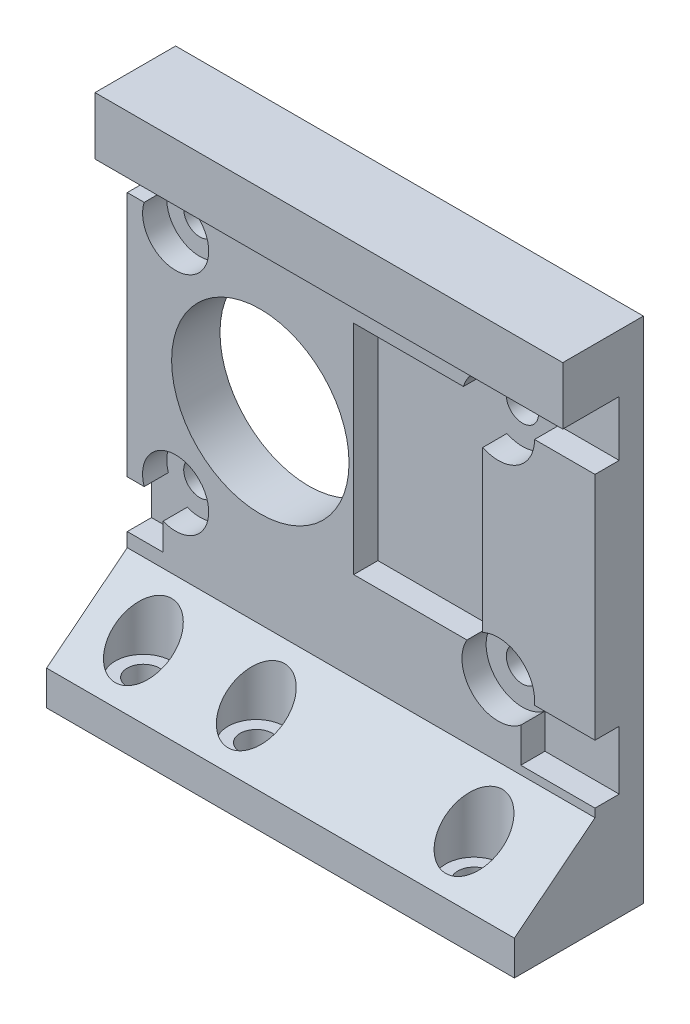
SolidWorks part; units mm, degrees
material "ABS"
ref_plane "Front Plane" through (0, 0, 0) normal (0, 0, 1) x (1, 0, 0)
ref_plane "Top Plane" through (0, 0, 0) normal (0, 1, 0) x (1, 0, 0)
ref_plane "Right Plane" through (0, 0, 0) normal (1, 0, 0) x (0, 0, -1)
sketch "Sketch1" plane through (0, 0, 0) normal (0, 0, 1) x (1, 0, 0)
  line L1 (-76.1871, 64.9281) -> (16.8129, 64.9281)
  line L2 (-76.1871, 64.9281) -> (-76.1871, -35.0719)
  line L3 (-76.1871, -35.0719) -> (16.8129, -35.0719)
  line L4 (16.8129, 64.9281) -> (16.8129, -35.0719)
  dimension "D1" = 93
  dimension "D2" = 100
extrude "Boss-Extrude2" add sketch "Sketch1" along normal blind 10 contours L1 L4 L3 L2
sketch "Sketch3" plane through (0, 0, 0) normal (0, 0, -1) x (-1, 0, 0)
  line L0 (76.1871, -35.0719) -> (-16.8129, -35.0719) construction
  line L1 (-16.8129, 64.9281) -> (-6.8129, 64.9281)
  line L2 (-16.8129, 64.9281) -> (-16.8129, -35.0719)
  line L3 (-16.8129, -35.0719) -> (-6.8129, -35.0719)
  line L4 (-6.8129, 64.9281) -> (-6.8129, -35.0719)
  line L5 (-16.8129, 64.9281) -> (-16.8129, -35.0719) construction
  dimension "D1" = 0
  dimension "D2" = 0
  dimension "D3" = 10
  dimension "D4" = 100
sketch "Sketch4" plane through (16.8129, 0, 0) normal (1, 0, 0) x (0, 0, -1)
  line L0 (-10, 64.9281) -> (-10, -35.0719) construction
  line L1 (-10, -5.0719) -> (0.01, -5.0719)
  line L2 (-10, -5.0719) -> (-10, -20.0719)
  line L3 (-10, -20.0719) -> (0.01, -20.0719)
  line L4 (0.01, -5.0719) -> (0.01, -20.0719)
  line L6 (-10, -35.0719) -> (0, -35.0719) construction
  dimension "D1" = 15
  dimension "D2" = 15
extrude "Boss-Extrude4" add sketch "Sketch4" along normal blind 24
sketch "Sketch5" plane through (0, -5.0719, 0) normal (0, 1, 0) x (1, 0, 0)
  line L0 (40.8129, -10) -> (16.8129, -10) construction
  line L2 (16.8129, 0) -> (16.8129, -10) construction
  circle A0 centre (26.8129, -5) radius 2
  dimension "D2" = 4
  dimension "D3" = 10
  dimension "D1" = 5
extrude "Cut-Extrude1" cut sketch "Sketch5" against normal blind 50
sketch "Sketch6" plane through (0, 0, 10) normal (0, 0, -1) x (-1, 0, 0)
  line L2 (76.1871, -35.0719) -> (-16.8129, -35.0719) construction
  line L3 (-16.8129, 64.9281) -> (-16.8129, -35.0719) construction
  circle A0 centre (-1.8129, -24.5719) radius 7.5
  dimension "D1" = 15
  dimension "D2" = 10.5
  dimension "D3" = 15
sketch "Sketch7" plane through (0, 0, 0) normal (0, 0, -1) x (-1, 0, 0)
  circle A0 centre (24.1871, 36.9281) radius 11
  circle A1 centre (24.1871, 36.9281) radius 9.3 construction
  dimension "D1" = 22
extrude "Cut-Extrude3" cut sketch "Sketch7" against normal blind 50
sketch "Sketch14" plane through (0, 0, 10) normal (0, 0, 1) x (1, 0, 0)
  line L0 (16.8129, 64.9281) -> (16.8129, -5.0719) construction
  line L1 (-44.6871, 15.7891) -> (16.8129, 15.7891)
  line L2 (-44.6871, 15.7891) -> (-44.6871, 57.7891)
  line L3 (-44.6871, 57.7891) -> (16.8129, 57.7891)
  line L4 (16.8129, 15.7891) -> (16.8129, 57.7891)
  dimension "D1" = 42
  dimension "D3" = 61.5
extrude "Cut-Extrude8" cut sketch "Sketch14" against normal blind 4
sketch "Sketch15" plane through (0, 0, 0) normal (0, 0, -1) x (-1, 0, 0)
  circle A0 centre (24.1871, 36.9281) radius 10
  circle A1 centre (24.1871, 36.9281) radius 11 construction
  dimension "D1" = 20
  dimension "D2" = 0
sketch "Sketch16" plane through (0, 0, 10) normal (0, 0, 1) x (1, 0, 0)
  line L0 (-43.6871, 56.9281) -> (14.3129, 56.9281) construction
  line L1 (-44.1871, 57.3281) -> (16.8129, 57.3281)
  line L2 (-44.1871, 57.3281) -> (-44.1871, 64.9281)
  line L3 (-44.1871, 64.9281) -> (16.8129, 64.9281)
  line L4 (16.8129, 57.3281) -> (16.8129, 64.9281)
  dimension "D1" = 0.4
sketch "Sketch17" plane through (0, 0, 10) normal (0, 0, 1) x (1, 0, 0)
  line L0 (16.8129, 15.7891) -> (16.8129, -5.0719) construction
  line L1 (-44.1871, 16.7281) -> (16.8129, 16.7281)
  line L2 (-44.1871, 16.7281) -> (-44.1871, -20.0719)
  line L3 (-44.1871, -20.0719) -> (16.8129, -20.0719)
  line L4 (16.8129, 16.7281) -> (16.8129, -20.0719)
  line L5 (-43.6871, 16.9281) -> (14.3129, 16.9281) construction
  line L6 (40.8129, -20.0719) -> (16.8129, -20.0719) construction
  line L9 (16.8129, -20.0719) -> (40.8129, -20.0719)
  line L10 (16.8129, -20.0719) -> (16.8129, -5.0719)
  line L11 (16.8129, -5.0719) -> (40.8129, -5.0719)
  line L12 (40.8129, -20.0719) -> (40.8129, -5.0719)
  line L13 (16.8129, -20.0719) -> (40.8129, -5.0719) construction
  line L14 (16.8129, -5.0719) -> (40.8129, -20.0719) construction
  point P16 (28.8129, -12.5719)
  dimension "D1" = 0.2
  dimension "D2" = 0
sketch "Sketch19" plane through (0, 0, 0) normal (0, 0, -1) x (-1, 0, 0)
  line L1 (-16.8129, 64.9281) -> (-16.8129, -35.0719) construction
  circle A0 centre (53.1871, 36.9281) radius 11
  circle A1 centre (24.1871, 36.9281) radius 10 construction
  dimension "D1" = 22
  dimension "D3" = 0
  dimension "D2" = 70
extrude "Cut-Extrude11" cut sketch "Sketch19" against normal blind 15
sketch "Sketch20" plane through (0, 0, 6) normal (0, 0, 1) x (1, 0, 0)
  circle A0 centre (-34.6871, 50.9281) radius 2
  circle A1 centre (5.3129, 50.9281) radius 2
  circle A2 centre (-34.6871, 22.9281) radius 2
  circle A3 centre (5.3129, 22.9281) radius 2
  arc A5 (-27.0471, 34.1316) -> (-27.0471, 39.7246) centre (-24.1871, 36.9281) ccw construction
  circle A6 centre (-24.1871, 36.9281) radius 11 construction
  dimension "D1" = 4
  dimension "D2" = 4
  dimension "D3" = 4
  dimension "D4" = 4
  dimension "D5" = 0
  dimension "D6" = 28
  dimension "D7" = 0
  dimension "D8" = 40
  dimension "D9" = 14
  dimension "D10" = 10.5
  dimension "D11" = 28
  dimension "D12" = 40
extrude "Cut-Extrude12" cut sketch "Sketch20" against normal blind 10
sketch "Sketch8" plane through (0, 64.9281, 0) normal (0, 1, 0) x (1, 0, 0)
  line L0 (-76.1871, -10) -> (16.8129, -10) construction
  line L5 (16.8129, 0) -> (12.3014, -10) construction
  line L6 (16.8129, -10) -> (7.8859, 0) construction
  line L8 (16.8129, -10) -> (16.8129, 0) construction
  line L9 (-76.1871, 0) -> (16.8129, 0) construction
  circle A0 centre (11.8129, -7) radius 1.4
  circle A1 centre (-13.1871, -7) radius 1.4
  point P4 (13.816, -6.6429)
  dimension "D1" = 25
  dimension "D2" = 5
  dimension "D3" = 2.8
  dimension "D4" = 7
  dimension "D5" = 7
sketch "Sketch21" plane through (0, 0, 0) normal (0, 0, -1) x (-1, 0, 0)
  line L1 (76.1871, 64.9281) -> (36.1871, 64.9281)
  line L2 (76.1871, 64.9281) -> (76.1871, 58.9281)
  line L3 (76.1871, 58.9281) -> (36.1871, 58.9281)
  line L4 (36.1871, 64.9281) -> (36.1871, 58.9281)
  dimension "D1" = 6
  dimension "D2" = 40
extrude "Boss-Extrude5" add sketch "Sketch21" along normal blind 27
sketch "Sketch22" plane through (0, 58.9281, 0) normal (0, -1, 0) x (1, 0, 0)
  line L0 (-76.1871, -27) -> (-76.1871, 0) construction
  line L1 (-36.1871, -27) -> (-76.1871, -27)
  line L2 (-36.1871, -27) -> (-36.1871, -20.7)
  line L3 (-36.1871, -20.7) -> (-76.1871, -20.7)
  line L4 (-76.1871, -27) -> (-76.1871, -20.7)
  dimension "D1" = 6.3
extrude "Boss-Extrude7" add sketch "Sketch22" along normal blind 40
sketch "Sketch23" plane through (0, 0, 10) normal (0, 0, 1) x (1, 0, 0)
  circle A0 centre (-53.1871, 36.9281) radius 8
  arc A1 (-44.6871, 43.9102) -> (-44.6871, 29.9459) centre (-53.1871, 36.9281) ccw construction
  dimension "D1" = 16
  dimension "D2" = 0
extrude "Cut-Extrude13" cut sketch "Sketch23" against normal blind 40
sketch "Sketch24" plane through (0, 0, 10) normal (0, 0, 1) x (1, 0, 0)
  line L1 (-76.1871, -35.0719) -> (42.0908, -35.0719)
  line L2 (-76.1871, -35.0719) -> (-76.1871, 6.7281)
  line L3 (-76.1871, 6.7281) -> (42.0908, 6.7281)
  line L4 (42.0908, -35.0719) -> (42.0908, 6.7281)
  dimension "D1" = 41.8
extrude "Cut-Extrude14" cut sketch "Sketch24" against normal blind 40
sketch "Sketch25" plane through (0, 0, 10) normal (0, 0, 1) x (1, 0, 0)
  line L5 (-44.6871, 29.9459) -> (-44.6871, 15.7891) construction
  line L6 (-76.1871, 6.7281) -> (-44.6871, 6.7281)
  line L7 (-76.1871, 6.7281) -> (-76.1871, 29.9281)
  line L8 (-76.1871, 29.9281) -> (-44.6871, 29.9281)
  line L9 (-44.6871, 6.7281) -> (-44.6871, 29.9281)
  arc A2 (-44.6871, 43.9102) -> (-44.6871, 29.9459) centre (-53.1871, 36.9281) ccw construction
  dimension "D1" = 7
extrude "Cut-Extrude15" cut sketch "Sketch25" against normal blind 20
sketch "Sketch26" plane through (0, 0, 6) normal (0, 0, 1) x (1, 0, 0)
  line L1 (-44.6871, 15.7891) -> (-36.2375, 15.7891)
  line L2 (-44.6871, 15.7891) -> (-44.6871, 21.6647)
  line L3 (-44.6871, 21.6647) -> (-36.2375, 21.6647)
  line L4 (-36.2375, 15.7891) -> (-36.2375, 21.6647)
  line L5 (-44.6871, 57.7891) -> (-36.2375, 57.7891)
  line L6 (-44.6871, 57.7891) -> (-44.6871, 52.1914)
  line L7 (-44.6871, 52.1914) -> (-36.2375, 52.1914)
  line L8 (-36.2375, 57.7891) -> (-36.2375, 52.1914)
  line L9 (6.8634, 52.1914) -> (14.3021, 52.1914)
  line L10 (6.8634, 52.1914) -> (6.8634, 57.7891)
  line L11 (6.8634, 57.7891) -> (14.3021, 57.7891)
  line L12 (14.3021, 52.1914) -> (14.3021, 57.7891)
  line L13 (6.8634, 20.9281) -> (14.3021, 20.9281)
  line L14 (6.8634, 20.9281) -> (6.8634, 15.7891)
  line L15 (6.8634, 15.7891) -> (14.3021, 15.7891)
  line L16 (14.3021, 20.9281) -> (14.3021, 15.7891)
  circle A0 centre (-34.6871, 22.9281) radius 2 construction
  circle A1 centre (-34.6871, 50.9281) radius 2 construction
  circle A2 centre (5.3129, 50.9281) radius 2 construction
  circle A3 centre (5.3129, 22.9281) radius 4
  circle A4 centre (5.3129, 50.9281) radius 4
  circle A5 centre (-34.6871, 50.9281) radius 4
  circle A6 centre (-34.6871, 22.9281) radius 4
  circle A7 centre (5.3129, 50.9281) radius 4
  circle A8 centre (5.3129, 22.9281) radius 4
  circle A9 centre (-34.6871, 50.9281) radius 4
  circle A10 centre (-34.6871, 22.9281) radius 4
  line M5 (-44.6871, 57.7891) -> (-44.6871, 43.9102)
  line M8 (-44.6871, 29.9281) -> (-44.6871, 15.7891)
  line M9 (-44.6871, 15.7891) -> (16.8129, 15.7891)
  line M11 (16.8129, 57.7891) -> (-44.6871, 57.7891)
  dimension "D1" = 8
  dimension "D2" = 8
  dimension "D3" = 8
  dimension "D4" = 8
extrude "Cut-Extrude18" cut sketch "Sketch26" against normal blind 3 contours A4 L9 L12 L10 M11 | A3 L14 L16 L13 M9 | A5 L8 L7 M11 M5 | A6 L3 L4 M8 M9
sketch "Sketch27" plane through (0, 0, 6) normal (0, 0, 1) x (1, 0, 0)
  circle A0 centre (5.3129, 50.9281) radius 4.1
  circle A1 centre (5.3129, 22.9281) radius 4
  circle A2 centre (-34.6871, 50.9281) radius 4.1
  circle A3 centre (-34.6871, 22.9281) radius 4.1
  dimension "D1" = 8.2
  dimension "D2" = 8.2
  dimension "D3" = 8
  dimension "D4" = 8.2
extrude "Cut-Extrude29" cut sketch "Sketch27" against normal blind 3
sketch "Sketch28" plane through (0, 0, 0) normal (0, 0, -1) x (-1, 0, 0)
  line L5 (-16.8129, 6.7281) -> (44.6871, 6.7281) construction
  line L6 (-16.8129, 64.9281) -> (12.6871, 64.9281)
  line L7 (-16.8129, 64.9281) -> (-16.8129, 6.7281)
  line L8 (-16.8129, 6.7281) -> (12.6871, 6.7281)
  line L9 (12.6871, 64.9281) -> (12.6871, 6.7281)
  circle A1 centre (34.6871, 22.9281) radius 2 construction
  dimension "D1" = 22
extrude "Cut-Extrude30" cut sketch "Sketch28" against normal blind 23
sketch "Sketch29" plane through (0, 15.7891, 0) normal (0, 1, 0) x (1, 0, 0)
  line L1 (-44.6871, -10) -> (-12.6871, -10)
  line L2 (-44.6871, -10) -> (-44.6871, -6)
  line L3 (-44.6871, -6) -> (-12.6871, -6)
  line L4 (-12.6871, -10) -> (-12.6871, -6)
extrude "Cut-Extrude31" cut sketch "Sketch29" against normal blind 23
sketch "Sketch31" plane through (0, 6.7281, 0) normal (0, -1, 0) x (1, 0, 0)
  line L1 (-44.6871, 6) -> (-12.6871, 6)
  line L2 (-44.6871, 6) -> (-44.6871, 0)
  line L3 (-44.6871, 0) -> (-12.6871, 0)
  line L4 (-12.6871, 6) -> (-12.6871, 0)
extrude "Boss-Extrude9" add sketch "Sketch31" along normal blind 6.6
sketch "Sketch32" plane through (0, 0, 6) normal (0, 0, 1) x (1, 0, 0)
  line L0 (-12.6871, 0.1281) -> (-12.6871, 57.7891) construction
  line L1 (-44.6871, 0.1281) -> (-12.6871, 0.1281)
  line L2 (-44.6871, 0.1281) -> (-44.6871, 6.1281)
  line L3 (-44.6871, 6.1281) -> (-12.6871, 6.1281)
  line L4 (-12.6871, 0.1281) -> (-12.6871, 6.1281)
  dimension "D1" = 6
extrude "Boss-Extrude10" add sketch "Sketch32" along normal blind 10
sketch "Sketch33" plane through (0, 6.1281, 0) normal (0, 1, 0) x (1, 0, 0)
  line L0 (-12.6871, -16) -> (-44.6871, -16) construction
  line L1 (-44.6871, -16) -> (-44.6871, -6) construction
  line L2 (-12.6871, -16) -> (-12.6871, -6) construction
  circle A0 centre (-33.6871, -11) radius 2
  circle A1 centre (-19.6871, -11) radius 2
  point P8 (-44.6871, -11)
  dimension "D1" = 4
  dimension "D2" = 4
  dimension "D3" = 0
  dimension "D4" = 5
  dimension "D5" = 11
  dimension "D6" = 7
extrude "Cut-Extrude32" cut sketch "Sketch33" against normal blind 10
sketch "Sketch34" plane through (-12.6871, 0, 0) normal (1, 0, 0) x (0, 0, -1)
  line L0 (-16, 6.1281) -> (-6, 6.1281)
  line L1 (-6, 6.1281) -> (-6, 14.0584)
  line L2 (-6, 6.1281) -> (-6, 57.7891) construction
  line L3 (-6, 14.0584) -> (-16, 6.1281)
extrude "Boss-Extrude11" add sketch "Sketch34" against normal up to vertex
sketch "Sketch35" plane through (0, 6.1281, 0) normal (0, -1, 0) x (1, 0, 0)
  circle A0 centre (-19.6871, 11) radius 3.5
  circle A1 centre (-33.6871, 11) radius 3.5
  dimension "D1" = 7
  dimension "D2" = 7
extrude "Cut-Extrude33" cut sketch "Sketch35" against normal blind 10
sketch "Sketch36" plane through (-36.1871, 0, 0) normal (1, 0, 0) x (0, 0, -1)
  line L1 (0, 64.9281) -> (27, 64.9281)
  line L2 (0, 64.9281) -> (0, 18.9281)
  line L3 (0, 18.9281) -> (27, 18.9281)
  line L4 (27, 64.9281) -> (27, 18.9281)
extrude "Cut-Extrude34" cut sketch "Sketch36" against normal blind 50
sketch "Sketch38" plane through (0, 0, 10) normal (0, 0, 1) x (1, 0, 0)
  line L0 (-76.1871, 64.9281) -> (-12.6871, 64.9281) construction
  line L1 (-76.1871, 29.9281) -> (-44.4371, 29.9281)
  line L2 (-76.1871, 29.9281) -> (-76.1871, 64.9281)
  line L3 (-76.1871, 64.9281) -> (-44.4371, 64.9281)
  line L4 (-44.4371, 29.9281) -> (-44.4371, 64.9281)
extrude "Cut-Extrude35" cut sketch "Sketch38" against normal blind 50
sketch "Sketch40" plane through (0, 0, 16) normal (0, 0, 1) x (1, 0, 0)
  line L1 (-44.6871, 0.1281) -> (-40.6871, 0.1281)
  line L2 (-44.6871, 0.1281) -> (-44.6871, 77.9464)
  line L3 (-44.6871, 77.9464) -> (-40.6871, 77.9464)
  line L4 (-40.6871, 0.1281) -> (-40.6871, 77.9464)
  dimension "D1" = 4
extrude "Cut-Extrude37" cut sketch "Sketch40" against normal blind 110
sketch "Sketch41" plane through (0, 0, 16) normal (0, 0, 1) x (1, 0, 0)
  line L1 (-40.6871, 0.1281) -> (-12.6871, 0.1281)
  line L2 (-40.6871, 0.1281) -> (-40.6871, 1.8481)
  line L3 (-40.6871, 1.8481) -> (-12.6871, 1.8481)
  line L4 (-12.6871, 0.1281) -> (-12.6871, 1.8481)
  dimension "D1" = 1.72
extrude "Cut-Extrude38" cut sketch "Sketch41" against normal blind 50
sketch "Sketch42" plane through (-12.6871, 0, 0) normal (1, 0, 0) x (0, 0, -1)
  line L0 (-10, 64.9281) -> (0, 64.9281)
  line L1 (0, 64.9281) -> (0, 1.8481)
  line L2 (0, 1.8481) -> (-16, 1.8481)
  line L3 (-16, 1.8481) -> (-16, 6.1281)
  line L4 (-16, 6.1281) -> (-6, 14.0584)
  line L5 (-6, 14.0584) -> (-6, 57.7891)
  line L6 (-6, 57.7891) -> (-10, 57.7891)
  line L7 (-10, 57.7891) -> (-10, 64.9281)
extrude "Boss-Extrude12" add sketch "Sketch42" along normal blind 30
sketch "Sketch43" plane through (0, 0, 6) normal (0, 0, 1) x (1, 0, 0)
  circle A0 centre (5.3129, 50.9281) radius 2
  circle A1 centre (5.3129, 22.9281) radius 2
  circle A2 centre (-34.6871, 50.9281) radius 2 construction
  circle A3 centre (-34.6871, 22.9281) radius 2 construction
  dimension "D1" = 4
  dimension "D2" = 4
  dimension "D3" = 40
  dimension "D4" = 40
  dimension "D5" = 28
  dimension "D6" = 0
extrude "Cut-Extrude39" cut sketch "Sketch43" against normal blind 30
sketch "Sketch44" plane through (0, 0, 6) normal (0, 0, 1) x (1, 0, 0)
  circle A0 centre (5.3129, 22.9281) radius 4.5
  circle A1 centre (5.3129, 50.9281) radius 4.5
  dimension "D1" = 9
  dimension "D2" = 9
extrude "Cut-Extrude40" cut sketch "Sketch44" against normal blind 3
sketch "Sketch45" plane through (0, 0, 6) normal (0, 0, 1) x (1, 0, 0)
  line L0 (17.3129, 57.7891) -> (-36.2375, 57.7891) construction
  line L1 (8.1062, 57.7891) -> (17.3129, 57.7891)
  line L2 (8.1062, 57.7891) -> (8.1062, 50.9281)
  line L3 (8.1062, 50.9281) -> (17.3129, 50.9281)
  line L4 (17.3129, 57.7891) -> (17.3129, 50.9281)
  line L5 (17.3129, 57.7891) -> (17.3129, 14.0584) construction
  line L7 (8.1062, 22.3817) -> (17.3129, 22.3817)
  line L8 (8.1062, 22.3817) -> (8.1062, 15.0922)
  line L9 (8.1062, 15.0922) -> (17.3129, 15.0922)
  line L10 (17.3129, 22.3817) -> (17.3129, 15.0922)
extrude "Cut-Extrude41" cut sketch "Sketch45" against normal blind 3
sketch "Sketch46" plane through (0, 0, 6) normal (0, 0, 1) x (1, 0, 0)
  line L1 (-12.6079, 52.2063) -> (3.3921, 52.2063)
  line L2 (-12.6079, 52.2063) -> (-12.6079, 25.2063)
  line L3 (-12.6079, 25.2063) -> (3.3921, 25.2063)
  line L4 (3.3921, 52.2063) -> (3.3921, 25.2063)
  point P4 (-12.1824, 46.9536)
  point P5 (0, 0)
  point P6 (0, 0)
  point P7 (0, 0)
  dimension "D1" = 16
  dimension "D2" = 27
extrude "Cut-Extrude42" cut sketch "Sketch46" against normal blind 3
sketch "Sketch47" plane through (0, 1.8481, 0) normal (0, -1, 0) x (1, 0, 0)
  line L0 (17.3129, 16) -> (17.3129, 0) construction
  circle A0 centre (7.3129, 11) radius 2
  circle A2 centre (-19.6871, 11) radius 2 construction
  dimension "D1" = 4
  dimension "D2" = 0
  dimension "D3" = 10
extrude "Cut-Extrude43" cut sketch "Sketch47" against normal blind 3
sketch "Sketch48" plane through (0, 4.8481, 0) normal (0, -1, 0) x (1, 0, 0)
  circle A0 centre (7.3129, 11) radius 3.5
  dimension "D1" = 7
extrude "Cut-Extrude44" cut sketch "Sketch48" against normal blind 23
